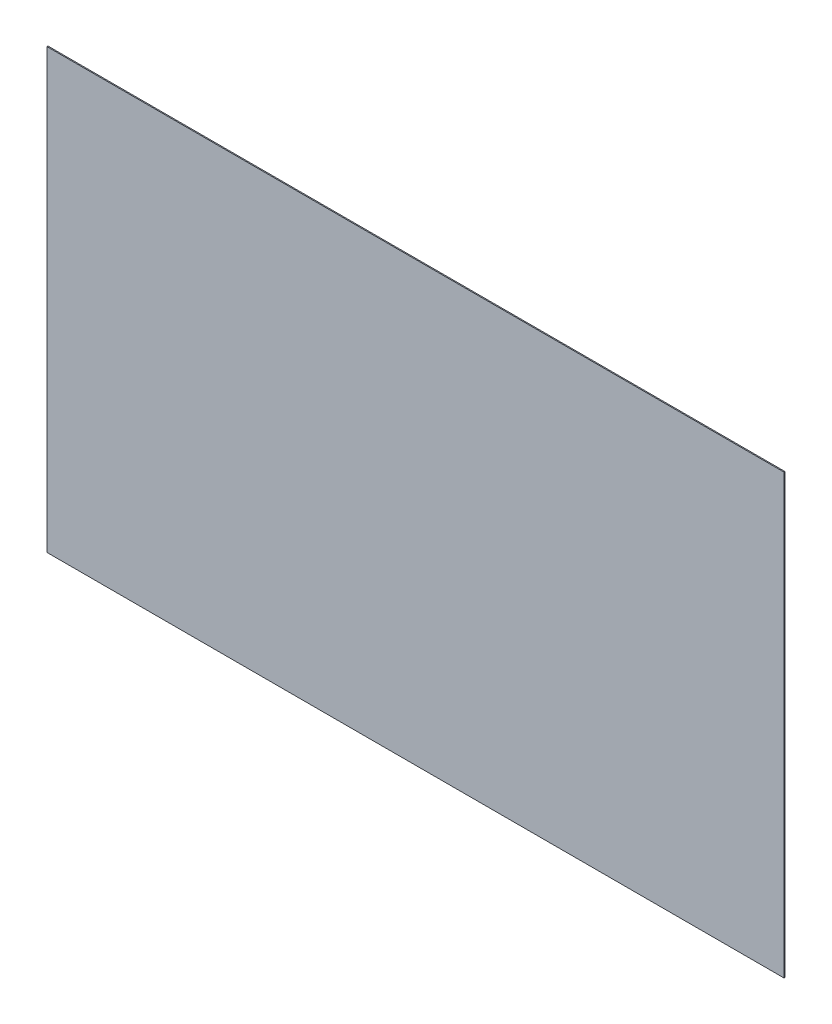
SolidWorks part; units mm, degrees
ref_plane "Front Plane" through (0, 0, 0) normal (0, 0, 1) x (1, 0, 0)
ref_plane "Top Plane" through (0, 0, 0) normal (0, 1, 0) x (1, 0, 0)
ref_plane "Right Plane" through (0, 0, 0) normal (1, 0, 0) x (0, 0, -1)
sketch "Sketch1" plane through (0, 0, 0) normal (0, 0, 1) x (1, 0, 0)
  line L1 (-32.5, -31.2) -> (39, -31.2)
  line L2 (-32.5, -31.2) -> (-32.5, 11.3)
  line L3 (-32.5, 11.3) -> (39, 11.3)
  line L4 (39, -31.2) -> (39, 11.3)
  dimension "D2" = 71.5
  dimension "D1" = 42.5
extrude "Extrude1" add sketch "Sketch1" along normal blind 0.1
